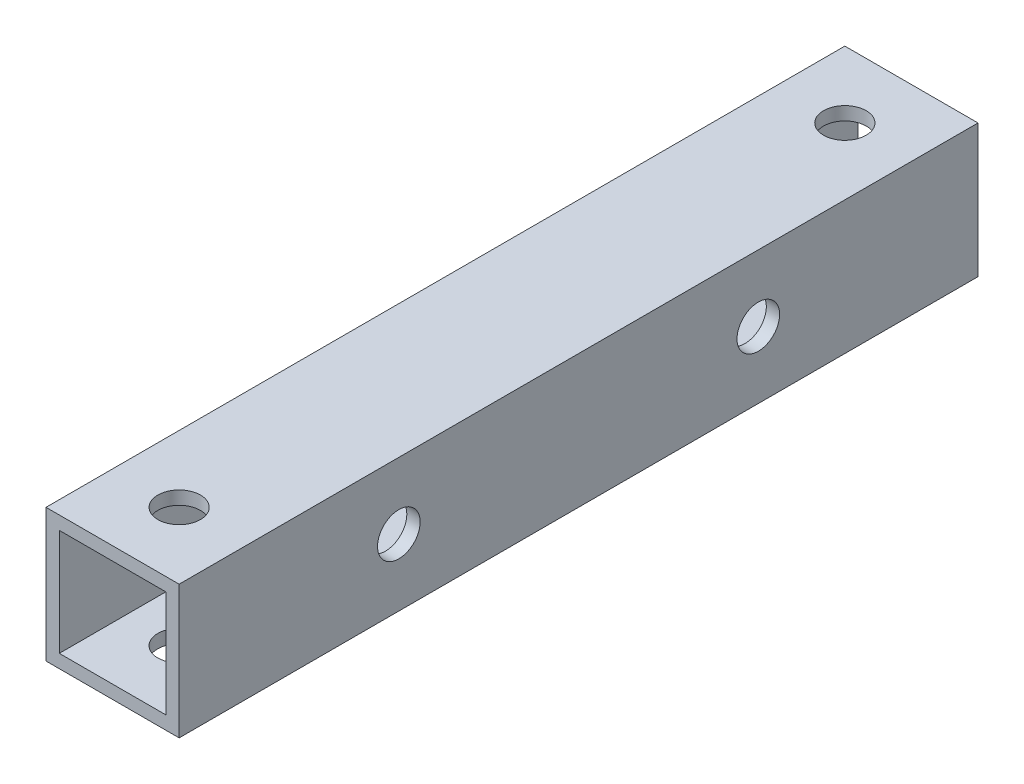
SolidWorks part; units mm, degrees
ref_plane "正面" through (0, 0, 0) normal (0, 0, 1) x (1, 0, 0)
ref_plane "平面" through (0, 0, 0) normal (0, 1, 0) x (1, 0, 0)
ref_plane "右側面" through (0, 0, 0) normal (1, 0, 0) x (0, 0, -1)
sketch "ｽｹｯﾁ1" plane through (0, 0, 0) normal (0, 0, 1) x (1, 0, 0)
  line L1 (-5, -5) -> (5, -5)
  line L2 (-5, -5) -> (-5, 5)
  line L3 (-5, 5) -> (5, 5)
  line L4 (5, -5) -> (5, 5)
  line L5 (-5, -5) -> (5, 5) construction
  line L6 (-5, 5) -> (5, -5) construction
  line L7 (-4, -4) -> (4, -4)
  line L8 (-4, -4) -> (-4, 4)
  line L9 (-4, 4) -> (4, 4)
  line L10 (4, -4) -> (4, 4)
  line L11 (-4, -4) -> (4, 4) construction
  line L12 (-4, 4) -> (4, -4) construction
  point P0 (0, 0)
  point P6 (0, 0)
  dimension "D1" = 1
  dimension "D2" = 10
  dimension "D3" = 10
extrude "ﾎﾞｽ - 押し出し1" add sketch "ｽｹｯﾁ1" along normal blind 30
sketch "ｽｹｯﾁ2" plane through (5, 0, 0) normal (1, 0, 0) x (0, 0, -1)
  line L0 (-30, -5) -> (0, -5) construction
  line L1 (0, -5) -> (0, 5) construction
  circle A0 centre (-13.5, 0) radius 1.6
  dimension "D1" = 3.2
  dimension "D2" = 5
  dimension "D3" = 13.5
extrude "ｶｯﾄ - 押し出し1" cut sketch "ｽｹｯﾁ2" against normal through all
sketch "ｽｹｯﾁ3" plane through (0, 5, 0) normal (0, 1, 0) x (1, 0, 0)
  line L0 (5, -30) -> (-5, -30) construction
  line L1 (5, -30) -> (5, 0) construction
  circle A0 centre (0, -25) radius 1.6
  dimension "D1" = 3.2
  dimension "D2" = 5
  dimension "D3" = 5
extrude "ｶｯﾄ - 押し出し2" cut sketch "ｽｹｯﾁ3" against normal through all
mirror "ﾐﾗｰ1" about plane through (0, 0, 0) normal (0, 0, -1) of "ｶｯﾄ - 押し出し1", "ﾎﾞｽ - 押し出し1", "ｶｯﾄ - 押し出し2"
